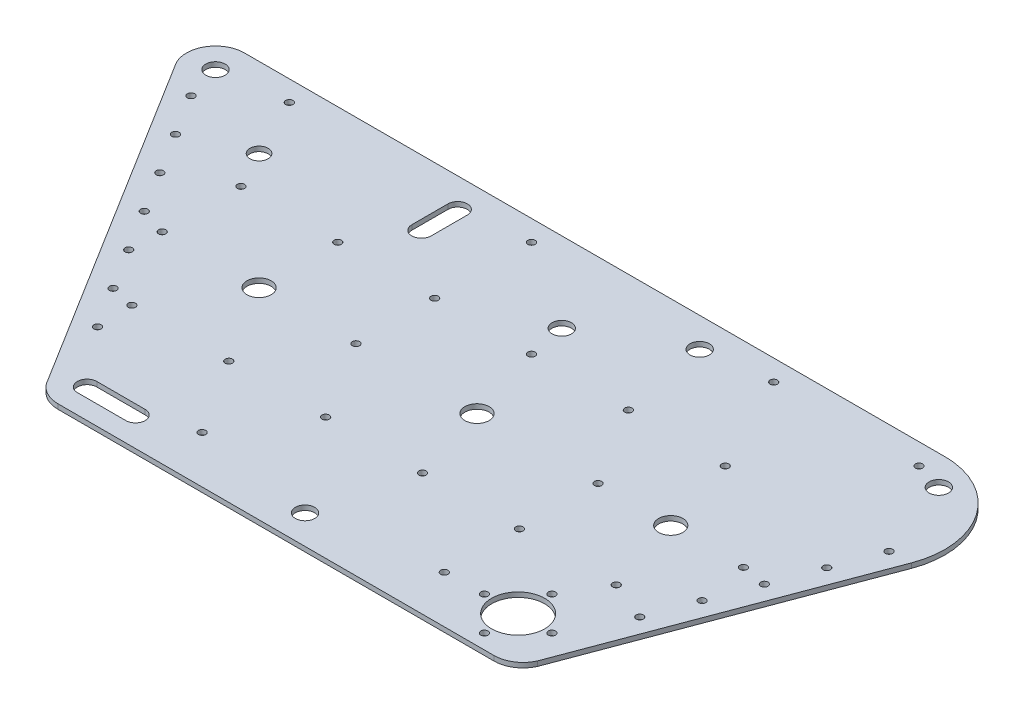
SolidWorks part; units mm, degrees
ref_plane "Front Plane" through (0, 0, 0) normal (0, 0, 1) x (1, 0, 0)
ref_plane "Top Plane" through (0, 0, 0) normal (0, 1, 0) x (1, 0, 0)
ref_plane "Right Plane" through (0, 0, 0) normal (1, 0, 0) x (0, 0, -1)
sketch "Sketch1" plane through (0, 0, 0) normal (0, 1, 0) x (1, 0, 0)
  line L0 (-106.4533, 145.5564) -> (183.7365, 145.8115)
  line L1 (161.6725, -19.0803) -> (-19.0794, -19.0803)
  line L2 (172.6268, -12.0507) -> (214.974, 100.7564)
  line L3 (-19.0794, -3.0127) -> (1.0042, -3.0127)
  line L4 (1.0042, -11.0465) -> (-19.0794, -11.0465)
  line L5 (-29.8256, -12.4811) -> (-116.5762, 127.1465)
  line L6 (-19.0794, -18.0761) -> (-18.9566, -18.0754)
  line L7 (-2.0084, 133.5622) -> (-2.0084, 118.5622)
  line L9 (-10.0418, 133.5622) -> (-10.0418, 118.5622)
  circle A0 centre (151.6308, 0.9921) radius 11
  ellipse E0 centre (-106.4428, 133.5622) end of major axis (-106.4428, 129.5453) minor radius 4.0167
  ellipse E1 centre (193.5523, 133.5077) end of major axis (193.5523, 137.5246) minor radius 4.0167
  ellipse E2 centre (-19.0794, -7.0296) end of major axis (-19.0794, -11.0465) minor radius 4.0167 (-19.0794, -3.0127) -> (-19.0794, -11.0465) ccw
  ellipse E3 centre (-6.0251, 118.5622) end of major axis (-6.0251, 122.5792) minor radius 4.0167 (-10.0418, 118.5622) -> (-2.0084, 118.5622) ccw
  ellipse E4 centre (-106.4428, 133.5622) end of major axis (-106.4428, 145.5564) minor radius 11.9935 (-106.4533, 145.5564) -> (-116.5762, 127.1465) ccw
  ellipse E5 centre (183.7644, 112.4735) end of major axis (183.7644, 145.8115) minor radius 33.3364 (214.974, 100.7564) -> (183.7351, 145.8115) ccw
  ellipse E6 centre (1.0042, -7.0296) end of major axis (1.0042, -3.0127) minor radius 4.0167 (1.0042, -11.0465) -> (1.0042, -3.0127) ccw
  ellipse E7 centre (151.6308, 14.9921) end of major axis (151.6308, 16.4984) minor radius 1.5063
  ellipse E8 centre (137.6308, 0.9921) end of major axis (137.6308, 2.4984) minor radius 1.5063
  ellipse E9 centre (165.6308, 0.9921) end of major axis (165.6308, 2.4984) minor radius 1.5063
  ellipse E10 centre (151.6308, -13.0079) end of major axis (151.6308, -11.5016) minor radius 1.5063
  ellipse E11 centre (-19.0794, -7.0296) end of major axis (-19.0794, 5.0211) minor radius 12.0501 (-29.8275, -12.4781) -> (-19.0794, -19.0803) ccw
  ellipse E12 centre (161.6725, -7.0296) end of major axis (161.6725, -19.0803) minor radius 12.0501 (161.6725, -19.0803) -> (172.6268, -12.0507) ccw
  ellipse E13 centre (121.5054, 0.5021) end of major axis (121.5054, 2.0085) minor radius 1.5063
  ellipse E14 centre (21.0877, 0.5021) end of major axis (21.0877, 2.0085) minor radius 1.5063
  ellipse E15 centre (121.5054, 64.2706) end of major axis (121.5054, 65.7769) minor radius 1.5063
  ellipse E16 centre (21.0877, 64.2706) end of major axis (21.0877, 65.7769) minor radius 1.5063
  ellipse E17 centre (-59.2465, 64.2706) end of major axis (-59.2465, 65.7769) minor radius 1.5063
  ellipse E18 centre (181.7561, 64.2706) end of major axis (181.7561, 65.7769) minor radius 1.5063
  ellipse E19 centre (-79.33, 137.077) end of major axis (-79.33, 138.5834) minor radius 1.5063
  ellipse E20 centre (21.0877, 137.077) end of major axis (21.0877, 138.5834) minor radius 1.5063
  ellipse E21 centre (121.5054, 137.077) end of major axis (121.5054, 138.5834) minor radius 1.5063
  ellipse E22 centre (61.2548, 96.9079) end of major axis (61.2548, 98.4143) minor radius 1.5063
  ellipse E23 centre (141.589, 96.9079) end of major axis (141.589, 98.4143) minor radius 1.5063
  ellipse E24 centre (161.6725, 31.6331) end of major axis (161.6725, 33.1395) minor radius 1.5063
  ellipse E25 centre (81.3384, 31.6331) end of major axis (81.3384, 33.1395) minor radius 1.5063
  ellipse E26 centre (-19.0794, 96.9079) end of major axis (-19.0794, 98.4143) minor radius 1.5063
  ellipse E27 centre (-39.1629, 31.6332) end of major axis (-39.1629, 33.1395) minor radius 1.5063
  ellipse E28 centre (-19.0794, 64.2706) end of major axis (-19.0794, 69.2917) minor radius 5.0209
  ellipse E29 centre (71.2966, 64.2706) end of major axis (71.2966, 69.2917) minor radius 5.0209
  ellipse E30 centre (151.6308, 64.2706) end of major axis (151.6308, 69.2917) minor radius 5.0209
  ellipse E31 centre (-102.1191, 119.0997) end of major axis (-102.1191, 120.6061) minor radius 1.5063
  ellipse E32 centre (-91.52, 102.0402) end of major axis (-91.52, 100.5338) minor radius 1.5063
  ellipse E33 centre (-80.9209, 84.9807) end of major axis (-80.9209, 83.4743) minor radius 1.5063
  ellipse E34 centre (-70.3215, 67.9206) end of major axis (-70.3215, 66.4143) minor radius 1.5063
  ellipse E35 centre (-59.7222, 50.8607) end of major axis (-59.7222, 49.3543) minor radius 1.5063
  ellipse E36 centre (-49.1231, 33.8011) end of major axis (-49.1231, 35.3074) minor radius 1.5063
  ellipse E37 centre (-38.5241, 16.7417) end of major axis (-38.5241, 15.2354) minor radius 1.5063
  ellipse E38 centre (206.1905, 100.2176) end of major axis (206.1905, 101.724) minor radius 1.5063
  ellipse E39 centre (199.1628, 81.4029) end of major axis (199.1628, 79.8965) minor radius 1.5063
  ellipse E40 centre (192.1353, 62.5883) end of major axis (192.1353, 64.0946) minor radius 1.5063
  ellipse E41 centre (185.1078, 43.7739) end of major axis (185.1078, 42.2675) minor radius 1.5063
  ellipse E42 centre (178.0803, 24.9595) end of major axis (178.0803, 26.4659) minor radius 1.5063
  ellipse E44 centre (181.7561, 137.077) end of major axis (181.7561, 138.5834) minor radius 1.5063
  ellipse E45 centre (21.0877, 96.9079) end of major axis (21.0877, 98.4143) minor radius 1.5063
  ellipse E46 centre (101.4219, 96.9079) end of major axis (101.4219, 98.4143) minor radius 1.5063
  ellipse E47 centre (-59.2465, 96.9079) end of major axis (-59.2465, 98.4143) minor radius 1.5063
  ellipse E48 centre (1.0042, 31.6332) end of major axis (1.0042, 30.1268) minor radius 1.5063
  ellipse E49 centre (41.1713, 31.6332) end of major axis (41.1713, 33.1395) minor radius 1.5063
  ellipse E50 centre (121.5054, 31.6331) end of major axis (121.5054, 30.1268) minor radius 1.5063
  ellipse E51 centre (-67.2799, 112.4735) end of major axis (-67.2799, 108.7076) minor radius 3.7657
  ellipse E52 centre (58.2423, 112.4735) end of major axis (58.2423, 116.4904) minor radius 4.0167
  ellipse E53 centre (-6.0251, 133.5622) end of major axis (-6.0251, 129.5453) minor radius 4.0167 (-2.0084, 133.5622) -> (-10.0418, 133.5622) ccw
  ellipse E54 centre (94.3926, 133.5077) end of major axis (90.3759, 133.5622) minor radius 4.0169
  ellipse E55 centre (71.2966, -7.0296) end of major axis (71.2966, -3.0127) minor radius 4.0167
  point P55 (0, 0)
  point P56 (0, 0)
  point P57 (151.6308, 0.5021)
  point P58 (0, 0)
  point P59 (0, 0)
  point P60 (0, 0)
  point P61 (0, 0)
  point P62 (151.6308, 0.5021)
  point P350 (0, 0)
  point P351 (0, 0)
  point P352 (0, 0)
  point P353 (0, 0)
  point P354 (0, 0)
  point P355 (0, 0)
  point P356 (0, 0)
  point P357 (0, 0)
  point P358 (0, 0)
  point P359 (0, 0)
  dimension "D2" = 22
  dimension "D1" = 15
  dimension "D3" = 14
  dimension "D4" = 14
  dimension "D5" = 14
  dimension "D6" = 14
extrude "Boss-Extrude1" add sketch "Sketch1" along normal blind 2
